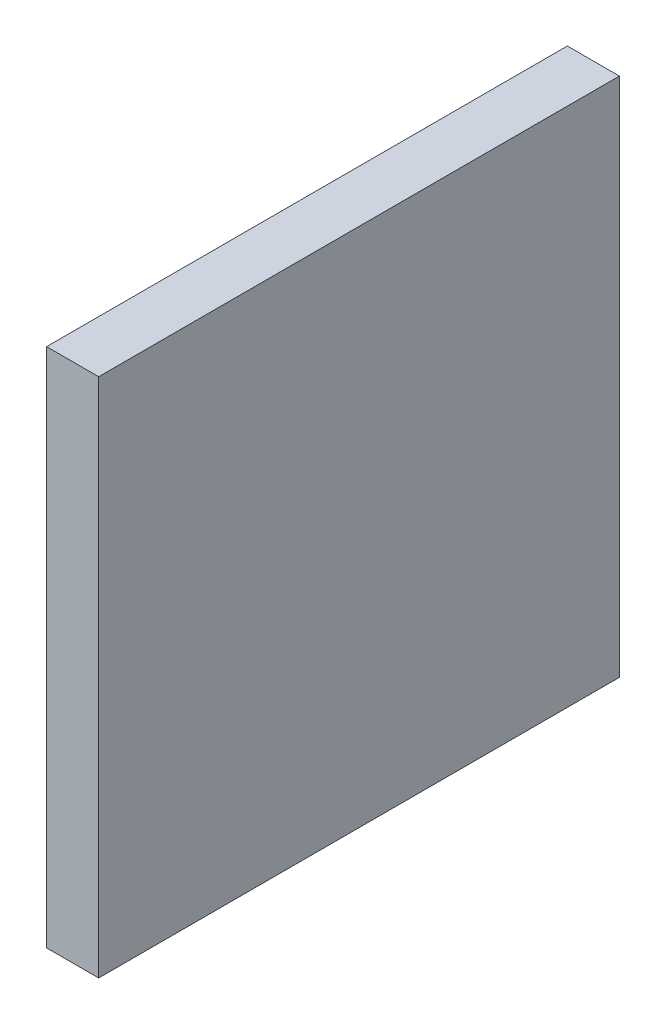
SolidWorks part; units mm, degrees
ref_plane "前视基准面" through (0, 0, 0) normal (0, 0, 1) x (1, 0, 0)
ref_plane "上视基准面" through (0, 0, 0) normal (0, 1, 0) x (1, 0, 0)
ref_plane "右视基准面" through (0, 0, 0) normal (1, 0, 0) x (0, 0, -1)
sketch "草图1" plane through (0, 0, 0) normal (1, 0, 0) x (0, 0, -1)
  line L1 (0, 0) -> (100, 0)
  line L2 (0, 0) -> (0, 100)
  line L3 (0, 100) -> (100, 100)
  line L4 (100, 0) -> (100, 100)
  dimension "D1" = 100
  dimension "D2" = 100
extrude "凸台-拉伸1" add sketch "草图1" along normal blind 10
